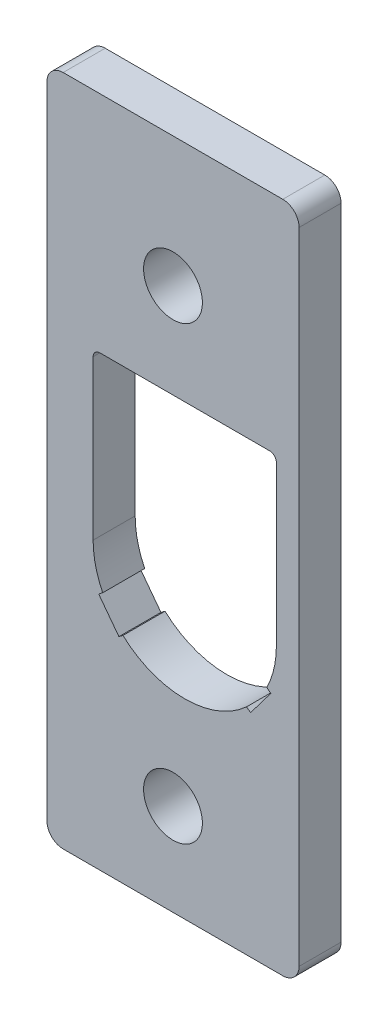
SolidWorks part; units mm, degrees
material "Acrylic (Medium-high impact)"
ref_plane "Front Plane" through (0, 0, 0) normal (0, 0, 1) x (1, 0, 0)
ref_plane "Top Plane" through (0, 0, 0) normal (0, 1, 0) x (1, 0, 0)
ref_plane "Right Plane" through (0, 0, 0) normal (1, 0, 0) x (0, 0, -1)
sketch "Sketch1" plane through (0, 0, 0) normal (0, 0, 1) x (1, 0, 0)
  line L0 (-13.843, 25.019) -> (-13.843, 0)
  line L1 (-12.3964, -6.161) -> (-13.005, -6.6195)
  line L2 (-9.3392, -10.218) -> (-9.9478, -10.6766)
  line L3 (9.3392, -10.218) -> (9.9478, -10.6766)
  line L4 (12.3964, -6.161) -> (13.005, -6.6195)
  line L5 (13.843, 0) -> (13.843, 25.019)
  line L6 (-13.843, 25.019) -> (13.843, 25.019)
  line L7 (-13.005, -6.6195) -> (-9.9478, -10.6766)
  line L8 (9.9478, -10.6766) -> (13.005, -6.6195)
  line L9 (0, -50.7997) -> (0, -133.9296) construction
  line L10 (-12.3964, -6.161) -> (-9.3392, -10.218) construction
  line L11 (9.3392, -10.218) -> (12.3964, -6.161) construction
  line L12 (-11.4764, -8.6481) -> (-10.8678, -8.1895) construction
  line L13 (11.4764, -8.6481) -> (10.8678, -8.1895) construction
  line L16 (17.272, -42.672) -> (-20.828, -42.672)
  line L17 (17.272, 58.928) -> (-20.828, 58.928)
  line L18 (17.272, -42.672) -> (17.272, 58.928)
  line L25 (-20.828, -42.672) -> (-20.828, 58.928)
  line L26 (-20.828, -42.672) -> (-20.828, 58.928)
  arc A0 (-13.843, 0) -> (-12.3964, -6.161) centre (0, 0) ccw
  arc A2 (-9.3392, -10.218) -> (9.3392, -10.218) centre (0, 0) ccw
  arc A4 (12.3964, -6.161) -> (13.843, 0) centre (0, 0) ccw
  point P29 (0, -13.843)
  dimension "D1" = 101.6
  dimension "D3" = 25.019
  dimension "D4" = 17.272
  dimension "D6" = 38.1
  dimension "D2" = 27.686
  dimension "D7" = 0.762
  dimension "D8" = 42.672
  dimension "D9" = 5.08
  dimension "D10" = 53
  dimension "D11" = 53
extrude "Boss-Extrude1" add sketch "Sketch1" along normal blind 6.35
sketch "Sketch2" plane through (0, 0, 6.35) normal (0, 0, 1) x (1, 0, 0)
  line L0 (-1.778, 58.928) -> (-1.778, -42.672) construction
  line L1 (17.272, 58.928) -> (-20.828, 58.928) construction
  line L2 (17.272, -42.672) -> (-20.828, -42.672) construction
  line L3 (-1.778, 39.3224) -> (-1.778, 56.388) construction
  line L4 (-1.778, -28.7814) -> (-1.778, -45.847) construction
  circle A0 centre (-1.778, 39.3224) radius 4.445
  circle A1 centre (-1.778, -28.7814) radius 4.445
  circle A2 centre (-1.778, 39.3224) radius 8.3344 construction
  circle A3 centre (-1.778, -28.7814) radius 8.3344 construction
  point P12 (-1.778, -20.447)
  point P15 (-1.778, 30.988)
  dimension "D1" = 8.89
  dimension "D4" = 16.6687
  dimension "D2" = 3.175
  dimension "D3" = 2.54
  dimension "D5" = 25.4
extrude "Cut-Extrude1" cut sketch "Sketch2" against normal up to next
fillet "Fillet5" radius 1.016 2 edges at (13.843, 25.019, 3.175) (-13.843, 25.019, 3.175)
fillet "Fillet6" radius 2.46 4 edges at (17.272, 58.928, 3.175) (17.272, -42.672, 3.175) (-20.828, -42.672, 3.175) (-20.828, 58.928, 3.175)
ref_plane "Midline" through (0, 0, 0) normal (1, 0, 0) x (0, 0, -1)
